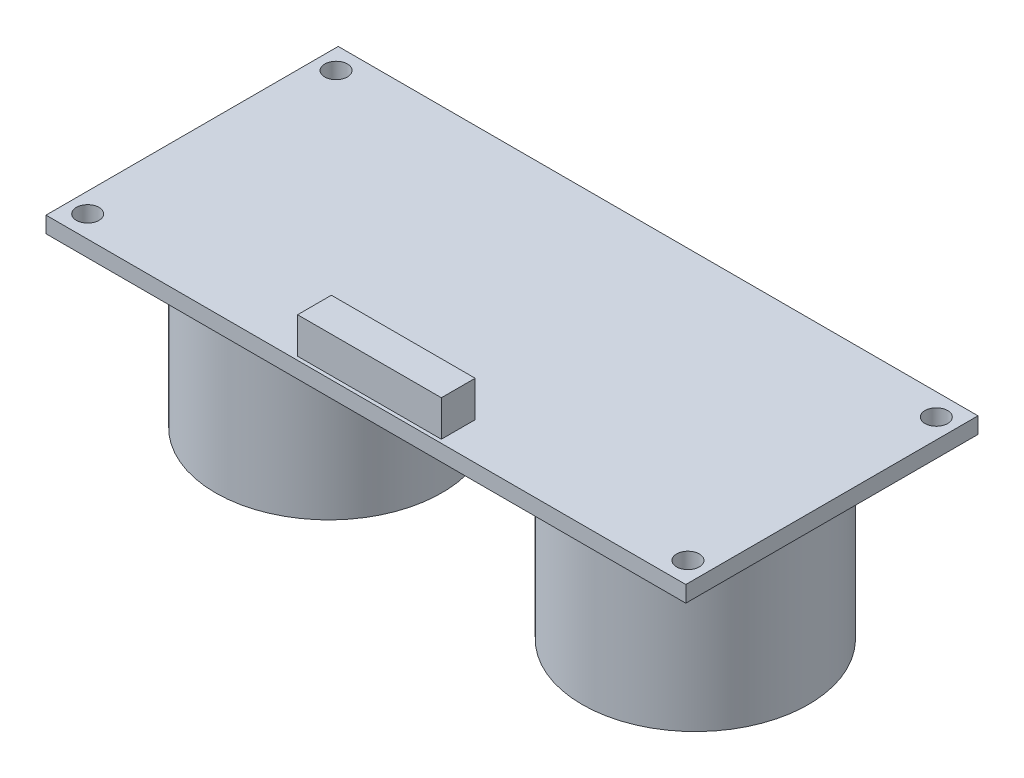
SolidWorks part; units mm, degrees
ref_plane "Front Plane" through (0, 0, 0) normal (0, 0, 1) x (1, 0, 0)
ref_plane "Top Plane" through (0, 0, 0) normal (0, 1, 0) x (1, 0, 0)
ref_plane "Right Plane" through (0, 0, 0) normal (1, 0, 0) x (0, 0, -1)
sketch "Sketch1" plane through (0, 0, 0) normal (0, 1, 0) x (1, 0, 0)
  line L0 (0, 10.3251) -> (22.606, 10.3251) construction
  line L1 (0, 0) -> (-22.606, 0)
  line L2 (0, 0) -> (0, 10.3251)
  line L3 (0, 10.3251) -> (-22.606, 10.3251)
  line L4 (-22.606, 0) -> (-22.606, 10.3251)
  line L5 (-22.606, 0) -> (-22.606, -10.3251) construction
  circle A0 centre (-21.209, 8.7757) radius 0.8
  point P9 (-21.209, 8.7757)
  point P10 (0, 0)
  dimension "D3" = 1.6
  dimension "D1" = 20.6502
  dimension "D2" = 45.212
  dimension "D4" = 21.209
  dimension "D5" = 8.7757
extrude "Boss-Extrude1" add sketch "Sketch1" along normal mid plane 1.143
mirror "Mirror1" of "Boss-Extrude1"
sketch "Sketch3" plane through (0, 0.5715, 0) normal (0, 1, 0) x (1, 0, 0)
  line L0 (0, -7.6835) -> (0, -10.0711)
  line L1 (-5.08, -10.0711) -> (0, -10.0711)
  line L2 (-5.08, -10.0711) -> (-5.08, -7.6835)
  line L3 (-5.08, -7.6835) -> (0, -7.6835)
  line L4 (5.08, -10.0711) -> (5.08, -7.6835) construction
  line L5 (0, -10.3251) -> (-22.606, -10.3251) construction
  line L6 (0, -10.0711) -> (5.08, -10.0711) construction
  line L7 (0, -7.6835) -> (5.08, -7.6835) construction
  line L8 (0, -10.3251) -> (0, 10.3251) construction
  dimension "D1" = 10.16
  dimension "D2" = 2.3876
  dimension "D3" = 0.254
extrude "Boss-Extrude2" add sketch "Sketch3" along normal blind 2.54
sketch "Sketch4" plane through (0, -0.5715, 0) normal (0, -1, 0) x (1, 0, 0)
  circle A0 centre (-12.954, 0) radius 8.001
  dimension "D1" = 16.002
  dimension "D2" = 12.954
extrude "Boss-Extrude3" add sketch "Sketch4" along normal blind 12.192
mirror "Mirror3" about plane through (0, 0, 0) normal (1, 0, 0) of bodies 110 103
